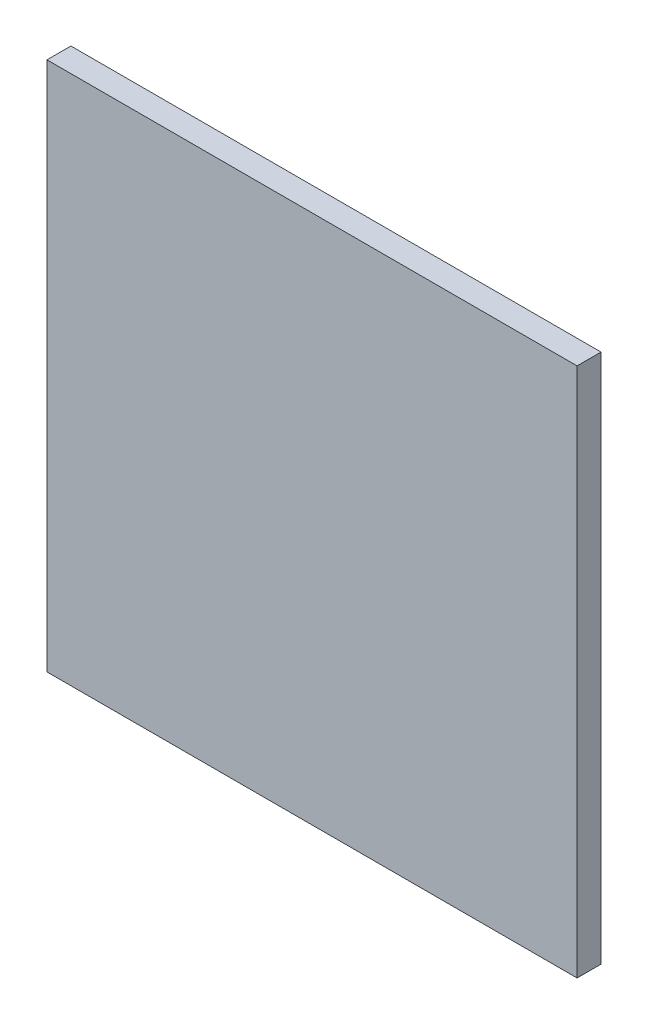
SolidWorks part; units mm, degrees
ref_plane "前视" through (0, 0, 0) normal (0, 0, 1) x (1, 0, 0)
ref_plane "上视" through (0, 0, 0) normal (0, 1, 0) x (1, 0, 0)
ref_plane "右视" through (0, 0, 0) normal (1, 0, 0) x (0, 0, -1)
sketch "草图1" plane through (0, 0, 0) normal (0, 0, 1) x (1, 0, 0)
  line L0 (-1611.3839, 0) -> (1936.635, 0) construction
  line L1 (135, 155) -> (155, 135)
  line L2 (0, 1418.2496) -> (0, -1054.9444) construction
  line L3 (-155, 155) -> (135, 155)
  line L4 (-155, 155) -> (-155, -135)
  line L5 (-135, -155) -> (155, -155)
  line L6 (155, 135) -> (155, -155)
  line L7 (-155, -135) -> (-135, -155)
  line L8 (-241.7498, -241.7498) -> (0, 0) construction
  line L9 (0, 0) -> (269.6196, 269.6196) construction
  line L10 (262.9093, -262.9093) -> (0, 0) construction
  line L11 (0, 0) -> (-278.609, 278.609) construction
  line L12 (0, 0) -> (-785, -619) construction
  line L13 (0, 0) -> (-50.8921, -40.1302) construction
  line L14 (0, 0) -> (171.8618, 135.5191) construction
  circle A0 centre (-113.1371, -113.1371) radius 13
  circle A1 centre (-78.5241, -61.919) radius 13
  circle A2 centre (78.5241, 61.919) radius 13
  circle A3 centre (113.1371, 113.1371) radius 13
  circle A4 centre (-70.7107, 70.7107) radius 13
  circle A5 centre (-113.1371, 113.1371) radius 13
  circle A6 centre (70.7107, -70.7107) radius 13
  circle A7 centre (113.1371, -113.1371) radius 13
  circle A8 centre (0, 0) radius 13
  dimension "D9" = 160
  dimension "D7" = 45
  dimension "D17" = 26
  dimension "D18" = 26
  dimension "D1" = 310
  dimension "D2" = 310
  dimension "D3" = 20
  dimension "D4" = 20
  dimension "D5" = 20
  dimension "D6" = 20
  dimension "D8" = 45
  dimension "D10" = 619
  dimension "D11" = 785
  dimension "D12" = 100
  dimension "D13" = 100
  dimension "D14" = 160
  dimension "D15" = 100
  dimension "D16" = 60
extrude "基体-拉伸" add sketch "草图1" along normal blind 14
sketch "草图3" plane through (0, 0, 14) normal (0, 0, 1) x (1, 0, 0)
  line L1 (-155, 155) -> (155, 155)
  line L2 (-155, 155) -> (-155, -155)
  line L3 (-155, -155) -> (155, -155)
  line L4 (155, 155) -> (155, -155)
extrude "凸台-拉伸1" add sketch "草图3" against normal blind 14
